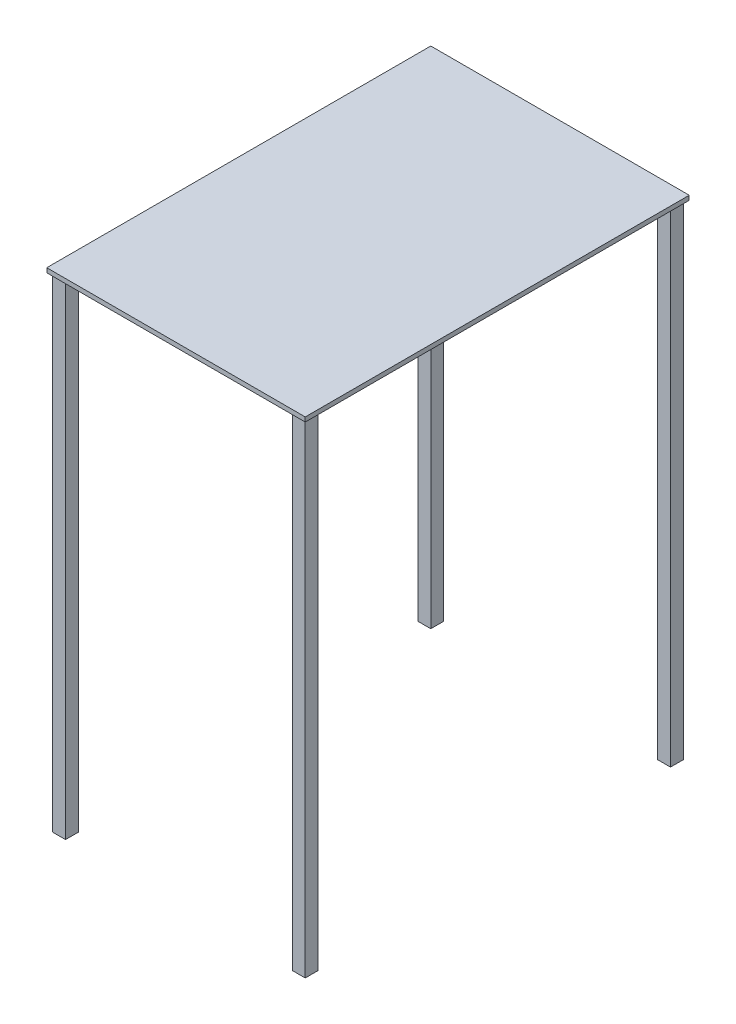
SolidWorks part; units mm, degrees
material "1060 Alloy"
ref_plane "Front Plane" through (0, 0, 0) normal (0, 0, 1) x (1, 0, 0)
ref_plane "Top Plane" through (0, 0, 0) normal (0, 1, 0) x (1, 0, 0)
ref_plane "Right Plane" through (0, 0, 0) normal (1, 0, 0) x (0, 0, -1)
sketch "Sketch1" plane through (0, 0, 0) normal (0, 1, 0) x (1, 0, 0)
  line L1 (-87.5, 130) -> (87.5, 130)
  line L2 (-87.5, 130) -> (-87.5, -130)
  line L3 (-87.5, -130) -> (87.5, -130)
  line L4 (87.5, 130) -> (87.5, -130)
  line L5 (-87.5, 130) -> (87.5, -130) construction
  line L6 (-87.5, -130) -> (87.5, 130) construction
  point P0 (0, 0)
  dimension "D1" = 175
  dimension "D2" = 260
extrude "Boss-Extrude1" add sketch "Sketch1" along normal blind 3
sketch "Sketch2" plane through (0, 0, 0) normal (0, -1, 0) x (1, 0, 0)
  line L0 (-87.5, -130) -> (87.5, 130)
  point P3 (0, 0)
sketch "Sketch4" plane through (0, 0, 0) normal (0, -1, 0) x (1, 0, 0)
  line L1 (85.5, -128) -> (76.8, -128)
  line L2 (85.5, -128) -> (85.5, -119.3)
  line L3 (85.5, -119.3) -> (76.8, -119.3)
  line L4 (76.8, -128) -> (76.8, -119.3)
  line L5 (85.5, -128) -> (76.8, -119.3) construction
  line L6 (85.5, -119.3) -> (76.8, -128) construction
  line L9 (85.5, -128) -> (85.5, -130) construction
  line L10 (85.5, -128) -> (87.5, -128) construction
  line L11 (87.5, 130) -> (87.5, -130) construction
  line L12 (87.5, -130) -> (-87.5, -130) construction
  point P0 (81.15, -123.65)
  dimension "D1" = 8.7
  dimension "D2" = 2
extrude "Boss-Extrude3" add sketch "Sketch4" along normal blind 328
mirror "Mirror3" about plane through (0, 0, 0) normal (0, 0, 1) of "Boss-Extrude3"
mirror "Mirror5" about plane through (0, 0, 0) normal (1, 0, 0) of "Mirror3", "Boss-Extrude3"
sketch "Sketch5" plane through (0, 0, 0) normal (0, -1, 0) x (1, 0, 0)
  line L0 (-87.5, 130) -> (87.5, -130)
  point P3 (0, 0)
sketch "Sketch6" plane through (0, 0, -130) normal (0, 0, -1) x (-1, 0, 0)
  line L0 (-87.5, 0) -> (87.5, 0)
  line L1 (-17, -2) -> (17, -2)
  line L2 (-17, -2) -> (-17, -37)
  line L3 (-17, -37) -> (17, -37)
  line L4 (17, -2) -> (17, -37)
  line L5 (-17, -2) -> (17, -37) construction
  line L6 (-17, -37) -> (17, -2) construction
  line L7 (0, 0) -> (0, -2) construction
  line L9 (-17, -2) -> (-11.26, -2)
  line L10 (-17, -2) -> (-17, -7.74)
  line L11 (-17, -7.74) -> (-11.26, -7.74)
  line L12 (-11.26, -2) -> (-11.26, -7.74)
  line L13 (-17, -2) -> (-11.26, -7.74) construction
  line L14 (-17, -7.74) -> (-11.26, -2) construction
  line L15 (11.26, -2) -> (17, -2)
  line L16 (11.26, -2) -> (11.26, -7.74)
  line L17 (11.26, -7.74) -> (17, -7.74)
  line L18 (17, -2) -> (17, -7.74)
  line L19 (11.26, -2) -> (17, -7.74) construction
  line L20 (11.26, -7.74) -> (17, -2) construction
  line L21 (-17, -31.26) -> (-11.26, -31.26)
  line L22 (-17, -31.26) -> (-17, -37)
  line L23 (-17, -37) -> (-11.26, -37)
  line L24 (-11.26, -31.26) -> (-11.26, -37)
  line L25 (-17, -31.26) -> (-11.26, -37) construction
  line L26 (-17, -37) -> (-11.26, -31.26) construction
  line L27 (11.26, -31.26) -> (17, -31.26)
  line L28 (11.26, -31.26) -> (11.26, -37)
  line L29 (11.26, -37) -> (17, -37)
  line L30 (17, -31.26) -> (17, -37)
  line L31 (11.26, -31.26) -> (17, -37) construction
  line L32 (11.26, -37) -> (17, -31.26) construction
  point P0 (0, -19.5)
  point P5 (-14.13, -4.87)
  point P8 (0, 0)
  point P17 (14.13, -4.87)
  point P22 (-14.13, -34.13)
  point P27 (14.13, -34.13)
  dimension "D1" = 34
  dimension "D2" = 35
  dimension "D3" = 2
  dimension "D4" = 5.74
extrude "Extrude-Thin1" add sketch "Sketch6" against normal blind 10 thin contours L4 L1 L2 L3 | L24 L21 L2 L3 | L27 L28 L3 L4 | L16 L17 L4 L1 | L12 L1 L2 L11
sketch "Sketch7" plane through (0, 0, -120) normal (0, 0, 1) x (1, 0, 0)
  line L0 (11.26, -2) -> (11.26, -7.74) construction
  line L1 (17, -2) -> (11.26, -2)
  line L2 (17, -2) -> (17, -7.74)
  line L3 (17, -7.74) -> (11.26, -7.74)
  line L4 (11.26, -2) -> (11.26, -7.74)
  line L5 (17, -2) -> (11.26, -7.74) construction
  line L6 (17, -7.74) -> (11.26, -2) construction
  line L7 (17, -31.26) -> (11.26, -31.26) construction
  line L8 (-11.26, -2) -> (-17, -2)
  line L9 (-11.26, -2) -> (-11.26, -7.74)
  line L10 (-11.26, -7.74) -> (-17, -7.74)
  line L11 (-17, -2) -> (-17, -7.74)
  line L12 (-11.26, -2) -> (-17, -7.74) construction
  line L13 (-11.26, -7.74) -> (-17, -2) construction
  line L14 (-11.26, -31.26) -> (-17, -31.26)
  line L15 (-11.26, -31.26) -> (-11.26, -37)
  line L16 (-11.26, -37) -> (-17, -37)
  line L17 (-17, -31.26) -> (-17, -37)
  line L18 (-11.26, -31.26) -> (-17, -37) construction
  line L19 (-11.26, -37) -> (-17, -31.26) construction
  line L20 (11.26, -31.26) -> (17, -31.26)
  line L21 (11.26, -31.26) -> (11.26, -37)
  line L22 (11.26, -37) -> (17, -37)
  line L23 (17, -31.26) -> (17, -37)
  line L24 (11.26, -31.26) -> (17, -37) construction
  line L25 (11.26, -37) -> (17, -31.26) construction
  line L26 (-11.26, -31.26) -> (-17, -31.26) construction
  line L27 (-11.26, -2) -> (-11.26, -7.74) construction
  point P0 (14.13, -4.87)
  point P7 (-14.13, -34.13)
  point P9 (-14.13, -4.87)
  point P18 (14.13, -34.13)
extrude "Boss-Extrude5" add sketch "Sketch7" against normal blind 8.5
sketch "Sketch9" plane through (0, 0, 0) normal (0, -1, 0) x (1, 0, 0)
  circle A0 centre (0, 0) radius 10.5
  dimension "D1" = 21
extrude "Extrude-Thin2" add sketch "Sketch9" along normal blind 18 thin thin type one direction reverse wall 4
ref_plane "Plane1" through (10.5, 0, 0) normal (1, 0, 0) x (0, 0, -1)
sketch "Sketch10" plane through (10.5, 0, 0) normal (1, 0, 0) x (0, 0, -1)
  line L0 (0, 0) -> (0, -10) construction
  line L1 (-130, 0) -> (130, 0) construction
  circle A0 centre (0, -10) radius 2.5
  dimension "D2" = 5
  dimension "D1" = 10
extrude "Cut-Extrude1" cut sketch "Sketch10" against normal through all both and the other way through all
sketch "Sketch11" plane through (0, 0, 0) normal (0, -1, 0) x (1, 0, 0)
  line L0 (-87.5, 80) -> (-72.5, 80) construction
  line L1 (-87.5, -130) -> (-87.5, 130) construction
  line L2 (-72.5, 130) -> (-72.5, 80) construction
  line L3 (-87.5, 130) -> (87.5, 130) construction
  circle A0 centre (-72.5, 80) radius 2.5
  point P1 (0, 0)
  dimension "D3" = 5
  dimension "D1" = 15
  dimension "D2" = 50
extrude "Boss-Extrude6" add sketch "Sketch11" along normal blind 3
sketch "Sketch12" plane through (0, -3, 0) normal (0, -1, 0) x (1, 0, 0)
  line L1 (-70.5, 80) -> (-71.5, 81.7321)
  line L2 (-71.5, 81.7321) -> (-73.5, 81.7321)
  line L3 (-73.5, 81.7321) -> (-74.5, 80)
  line L4 (-74.5, 80) -> (-73.5, 78.2679)
  line L5 (-73.5, 78.2679) -> (-71.5, 78.2679)
  line L6 (-71.5, 78.2679) -> (-70.5, 80)
  circle A0 centre (-72.5, 80) radius 1.7321 construction
  circle A2 centre (-72.5, 80) radius 2.5 construction
  point P1 (0, 0)
  point P11 (0, 0)
  point P14 (0, 0)
  dimension "D1" = 2
extrude "Cut-Extrude2" cut sketch "Sketch12" against normal blind 1
mirror "Mirror6" about plane through (0, 0, 0) normal (1, 0, 0) of "Cut-Extrude2", "Boss-Extrude6"
mirror "Mirror7" about plane through (0, 0, 0) normal (0, 0, 1) of "Mirror6", "Boss-Extrude6", "Cut-Extrude2"
